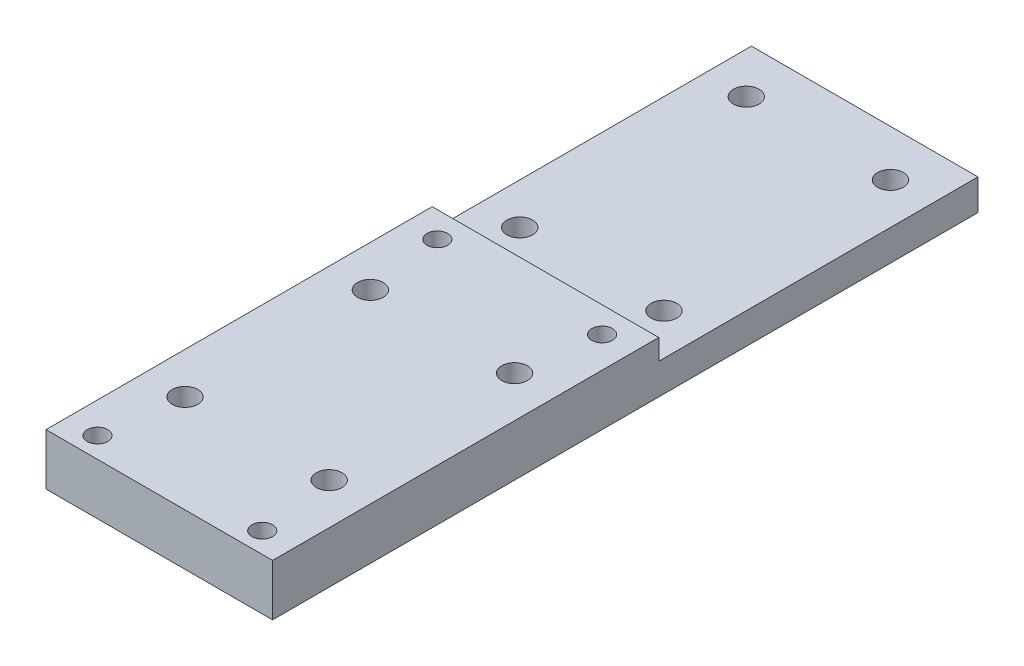
SolidWorks part; units mm, degrees
ref_plane "Front Plane" through (0, 0, 0) normal (0, 0, 1) x (1, 0, 0)
ref_plane "Top Plane" through (0, 0, 0) normal (0, 1, 0) x (1, 0, 0)
ref_plane "Right Plane" through (0, 0, 0) normal (1, 0, 0) x (0, 0, -1)
sketch "Sketch1" plane through (0, 0, 0) normal (0, 1, 0) x (1, 0, 0)
  line L1 (-22, 68.5) -> (22, 68.5)
  line L2 (-22, 68.5) -> (-22, -68.5)
  line L3 (-22, -68.5) -> (22, -68.5)
  line L4 (22, 68.5) -> (22, -68.5)
  line L5 (-22, 68.5) -> (22, -68.5) construction
  line L6 (-22, -68.5) -> (22, 68.5) construction
  circle A0 centre (-14, 59.5) radius 2.5
  circle A1 centre (14, 59.5) radius 2.5
  circle A2 centre (14, 15.5) radius 2.5
  circle A3 centre (-14, 15.5) radius 2.5
  circle A4 centre (14, -13.5) radius 2.5
  circle A5 centre (-14, -13.5) radius 2.5
  circle A6 centre (-14, -49.5) radius 2.5
  circle A7 centre (14, -49.5) radius 2.5
  circle A8 centre (-16, 1.5) radius 2
  circle A9 centre (16, 1.5) radius 2
  circle A10 centre (-16, -64.5) radius 2
  circle A11 centre (16, -64.5) radius 2
  point P0 (0, 0)
  dimension "D3" = 5
  dimension "D12" = 4
  dimension "D1" = 137
  dimension "D2" = 44
  dimension "D4" = 9
  dimension "D5" = 8
  dimension "D10" = 6
  dimension "D11" = 15
  dimension "D6" = 2
  dimension "D7" = 2
  dimension "D8" = 2
  dimension "D9" = 2
  dimension "D13" = 2
  dimension "D14" = 2
extrude "Boss-Extrude1" add sketch "Sketch1" along normal blind 10
sketch "Sketch2" plane through (22, 0, 0) normal (1, 0, 0) x (0, 0, -1)
  line L1 (-68.5, 10) -> (68.5, 10) construction
  line L2 (6.5, 10) -> (68.5, 10)
  line L3 (6.5, 10) -> (6.5, 6)
  line L4 (6.5, 6) -> (68.5, 6)
  line L5 (68.5, 10) -> (68.5, 6)
  line L6 (68.5, 10) -> (68.5, 0) construction
  dimension "D1" = 4
  dimension "D2" = 62
extrude "Cut-Extrude1" cut sketch "Sketch2" against normal through all
